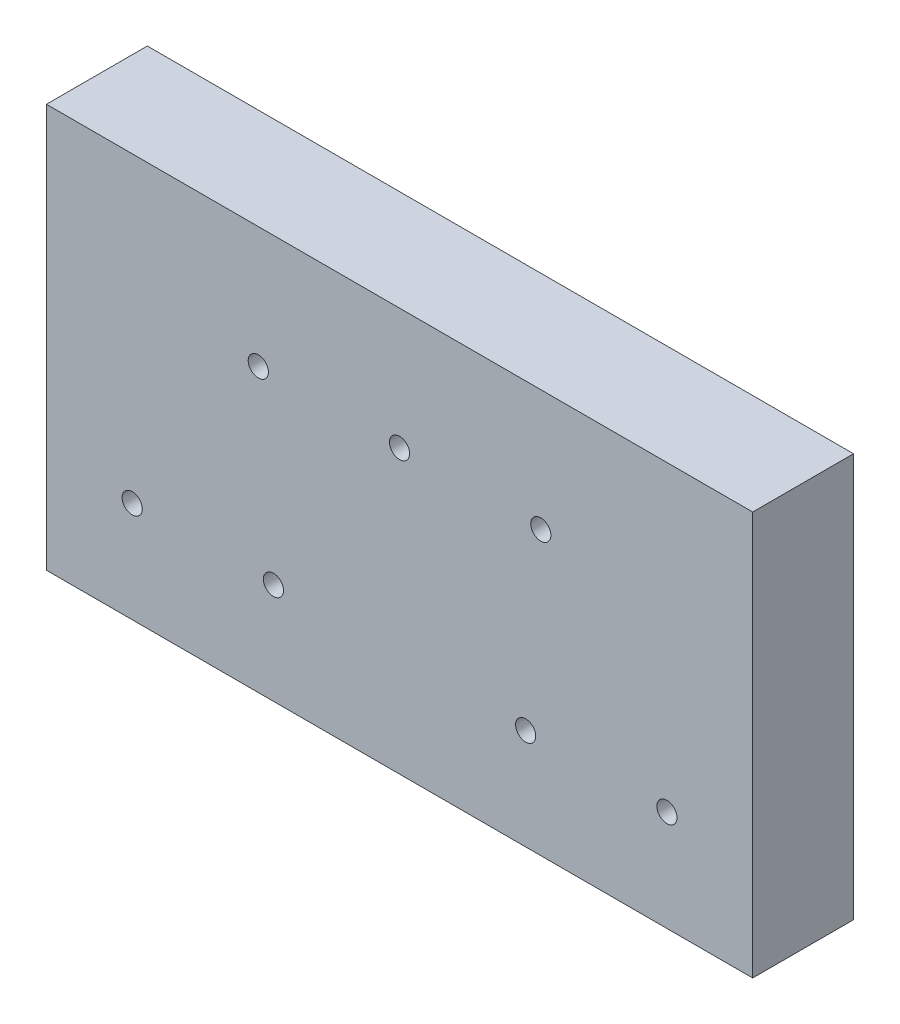
SolidWorks part; units mm, degrees
ref_plane "Front Plane" through (0, 0, 0) normal (0, 0, 1) x (1, 0, 0)
ref_plane "Top Plane" through (0, 0, 0) normal (0, 1, 0) x (1, 0, 0)
ref_plane "Right Plane" through (0, 0, 0) normal (1, 0, 0) x (0, 0, -1)
sketch "Sketch1" plane through (0, 0, 0) normal (0, 0, 1) x (1, 0, 0)
  line L0 (0, 45.315) -> (0, -47.1646) construction
  line L1 (-35, 20) -> (35, 20)
  line L2 (-35, 20) -> (-35, -20)
  line L3 (-35, -20) -> (35, -20)
  line L4 (35, 20) -> (35, -20)
  line L5 (-14, 41.0467) -> (-14, -27.3882) construction
  line L6 (14, 41.0467) -> (14, -27.3882) construction
  line L7 (-62.8862, 8) -> (40.242, 8) construction
  line L8 (-79.1057, 0) -> (82.6626, 0) construction
  line L9 (-62.7794, -10) -> (40.3488, -10) construction
  line L10 (-12.5, -13.9093) -> (-12.5, -5.2269) construction
  line L12 (-26.5, -13.9093) -> (-26.5, -5.2269) construction
  line L13 (12.5, -13.9093) -> (12.5, -5.2269) construction
  line L14 (26.5, -13.9093) -> (26.5, -5.2269) construction
  circle A0 centre (-14, 8) radius 1
  circle A1 centre (14, 8) radius 1
  circle A2 centre (0, 8) radius 1
  circle A3 centre (-26.5, -10) radius 1
  circle A4 centre (-12.5, -10) radius 1
  circle A5 centre (26.5, -10) radius 1
  circle A6 centre (12.5, -10) radius 1
  dimension "D7" = 2
  dimension "D8" = 2
  dimension "D10" = 2
  dimension "D12" = 2
  dimension "D1" = 70
  dimension "D2" = 40
  dimension "D3" = 14
  dimension "D4" = 14
  dimension "D5" = 12
  dimension "D6" = 10
  dimension "D9" = 14
  dimension "D11" = 25
extrude "Boss-Extrude1" add sketch "Sketch1" along normal blind 10
